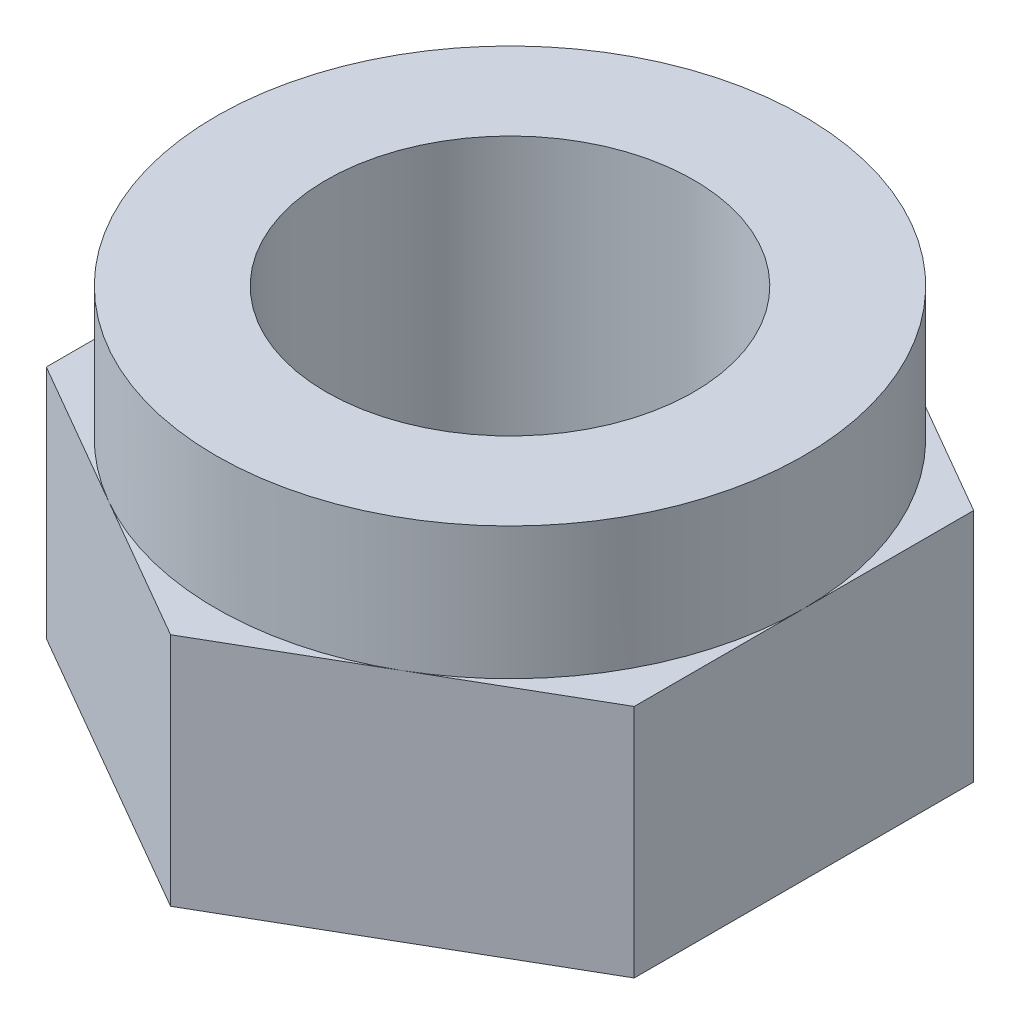
SolidWorks part; units mm, degrees
material "AISI 304"
ref_plane "前视基准面" through (0, 0, 0) normal (0, 0, 1) x (1, 0, 0)
ref_plane "上视基准面" through (0, 0, 0) normal (0, 1, 0) x (1, 0, 0)
ref_plane "右视基准面" through (0, 0, 0) normal (1, 0, 0) x (0, 0, -1)
sketch "草图1" plane through (0, 0, 0) normal (0, 1, 0) x (1, 0, 0)
  line L1 (0, -4.6188) -> (4, -2.3094)
  line L2 (4, -2.3094) -> (4, 2.3094)
  line L3 (4, 2.3094) -> (0, 4.6188)
  line L4 (0, 4.6188) -> (-4, 2.3094)
  line L5 (-4, 2.3094) -> (-4, -2.3094)
  line L6 (-4, -2.3094) -> (0, -4.6188)
  circle A0 centre (0, 0) radius 2.5
  circle A1 centre (0, 0) radius 4 construction
  dimension "D1" = 5
  dimension "D2" = 8
extrude "凸台-拉伸1" add sketch "草图1" along normal blind 3.2
sketch "草图2" plane through (0, 3.2, 0) normal (0, 1, 0) x (1, 0, 0)
  line L0 (0, 4.6188) -> (-4, 2.3094) construction
  circle A0 centre (0, 0) radius 2.5 construction
  circle A1 centre (0, 0) radius 2.5
  circle A2 centre (0, 0) radius 4
extrude "凸台-拉伸2" add sketch "草图2" along normal blind 1.8
equation "\"内径\" = 5"
equation "\"厚\" = 5"
equation "\"螺纹厚\" = 3.2"
equation "\"六角\"= 8"
equation "\"D1@草图1\"= \"内径\""
equation "\"D2@草图1\"= \"六角\""
equation "\"D1@凸台-拉伸1\"= \"螺纹厚\""
equation "\"胶厚\"= \"厚\" - \"螺纹厚\""
equation "\"D1@凸台-拉伸2\"= \"胶厚\""
